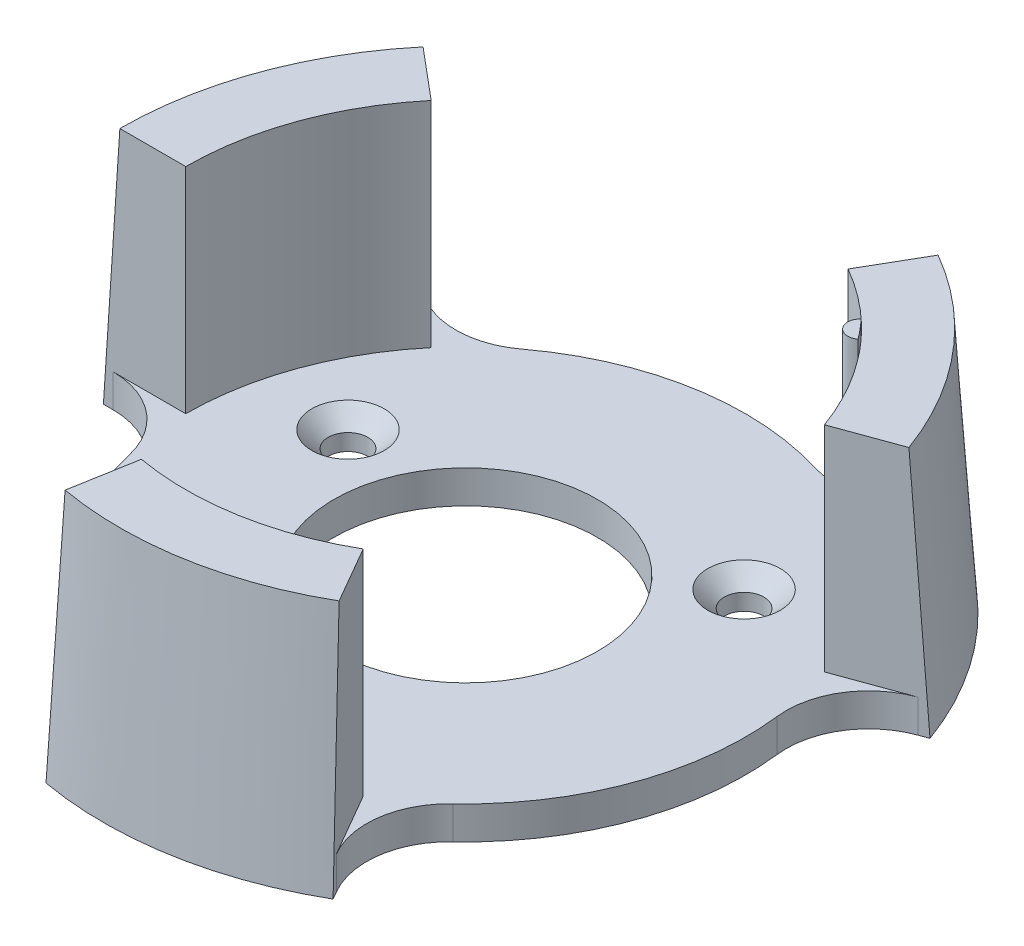
SolidWorks part; units mm, degrees
ref_plane "Front Plane" through (0, 0, 0) normal (0, 0, 1) x (1, 0, 0)
ref_plane "Top Plane" through (0, 0, 0) normal (0, 1, 0) x (1, 0, 0)
ref_plane "Right Plane" through (0, 0, 0) normal (1, 0, 0) x (0, 0, -1)
sketch "Sketch1" plane through (0, 0, 0) normal (0, 1, 0) x (1, 0, 0)
  circle A0 centre (0, 0) radius 8
  circle A1 centre (0, 0) radius 17
  dimension "D1" = 16
  dimension "D2" = 34
extrude "Boss-Extrude4" add sketch "Sketch1" along normal blind 2 contours A1 | A0
sketch "Sketch5" plane through (0, 0, 0) normal (0, 0, 1) x (1, 0, 0)
  line L0 (-17, 0) -> (-22, 0)
  line L1 (-17, 0) -> (-17, 15)
  line L2 (-17, 15) -> (-21, 15)
  line L3 (-21, 15) -> (-22, 0)
  line L4 (-17, 0) -> (17, 0) construction
  line L5 (0, 9.8137) -> (0, -8.5535) construction
  dimension "D1" = 15
  dimension "D2" = 5
  dimension "D3" = 4
revolve "Revolve2" add sketch "Sketch5" angle 40 about L5
pattern_circular "CirPattern1" count 3 over 360 about axis through (0, 0, 0) along (0, 1, 0) of "Revolve2"
fillet "Fillet1" radius 5 6 edges at (8.5, 1, 14.7224) (15.9748, 1, -5.8143) (8.5, 1, -14.7224) (-13.0228, 1, -10.9274) (-17, 1, 0) (-2.952, 1, 16.7417)
sketch "Sketch6" plane through (0, 2, 0) normal (0, 1, 0) x (1, 0, 0)
  line L0 (-15.9748, 5.8143) -> (20.5236, -7.47) construction
  line L1 (13.0228, 10.9274) -> (-17.0854, -14.3363) construction
  line L2 (2.952, -16.7417) -> (-4.6806, 26.545) construction
  arc A0 (-13.0228, 10.9274) -> (-17, 0) centre (0, 0) ccw construction
  arc A1 (15.9748, 5.8143) -> (8.5, 14.7224) centre (0, 0) ccw construction
  arc A2 (-2.952, -16.7417) -> (8.5, -14.7224) centre (0, 0) ccw construction
  circle A3 centre (0, 0) radius 12 construction
  point P19 (-11.2361, 4.0896)
  point P20 (2.0838, -11.8177)
  point P22 (0.0402, -0.0146)
  point P23 (9.1925, 7.7135)
  dimension "D1" = 24
hole_wizard "CSK for M2 Countersunk Flat Head Screw1" positions "Sketch12" profile "Sketch13" countersink size "M2" standard "ISO" end condition through all
sketch "Sketch12" plane through (0, 2, 0) normal (0, 1, 0) x (1, 0, 0)
  point P0 (2.0838, -11.8177)
  point P3 (9.1925, 7.7135)
  point P6 (-11.2361, 4.0896)
sketch "Sketch13" plane through (2.0838, 2, 11.8177) normal (1, 0, 0) x (0, 0, 1)
  line L0 (0, 0) -> (0, 2)
  line L1 (0, 2) -> (1.2, 2)
  line L2 (1.2, 2) -> (1.2, 1)
  line L3 (1.2, 1) -> (2.2, 0)
  line L5 (2.2, 0) -> (0, 0)
  line L6 (-1.2, 1) -> (-2.2, 0) construction
  line L11 (0, -6.35) -> (0, 107.95) construction
  dimension "Thru Hole Dia." = 2.4
  dimension "Thru Hole Depth" = 2
  dimension "Near C'Sink Dia." = 4.4
  dimension "Near C'Sink Angle" = 90
sketch "Sketch18" plane through (0, 0, 0) normal (0, -1, 0) x (1, 0, 0)
  line L0 (13.0228, -10.9274) -> (-17.0854, 14.3363) construction
sketch "Sketch22" plane through (0, 15, 0) normal (0, 1, 0) x (1, 0, 0)
  line L0 (2.952, -16.7417) -> (3.6466, -20.681) construction
  arc A0 (-2.952, -16.7417) -> (8.5, -14.7224) centre (0, 0) ccw construction
  arc A1 (-3.6466, -20.681) -> (10.5, -18.1865) centre (0, 0) ccw construction
sketch "Sketch24" plane through (0, 2, 0) normal (0, 1, 0) x (1, 0, 0)
  arc A0 (12.5281, 11.4912) -> (13.4921, 10.3423) centre (13.0228, 10.9274) ccw
  arc A1 (15.9748, 5.8143) -> (8.5, 14.7224) centre (0, 0) ccw construction
  arc A2 (13.4921, 10.3423) -> (12.5281, 11.4912) centre (0, 0) ccw
extrude "Boss-Extrude6" add sketch "Sketch24" along normal blind 14
